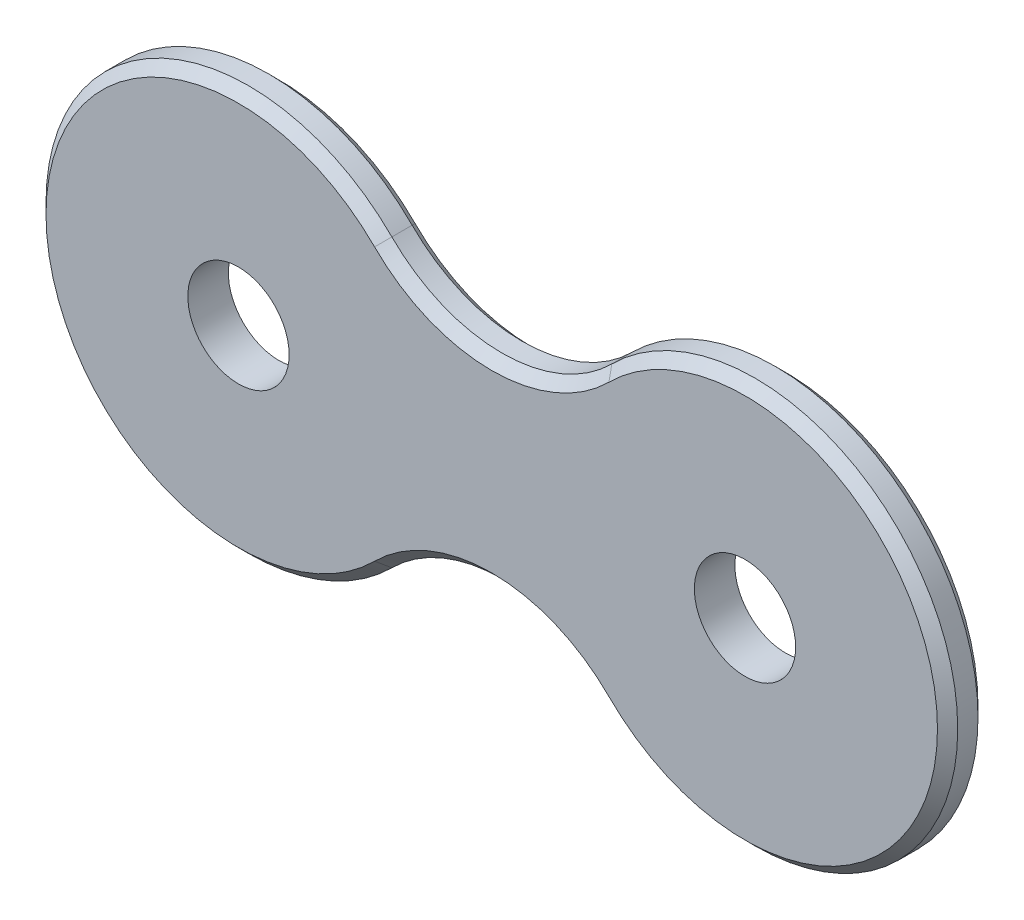
SolidWorks part; units mm, degrees
ref_plane "Front Plane" through (0, 0, 0) normal (0, 0, 1) x (1, 0, 0)
ref_plane "Top Plane" through (0, 0, 0) normal (0, 1, 0) x (1, 0, 0)
ref_plane "Right Plane" through (0, 0, 0) normal (1, 0, 0) x (0, 0, -1)
sketch "Sketch1" plane through (0, 0, 0) normal (0, 0, 1) x (1, 0, 0)
  arc A0 (17.9289, -7.0711) -> (17.9289, 7.0711) centre (25, 0) ccw
  circle A1 centre (25, 0) radius 2.5
  arc A2 (7.0711, 7.0711) -> (7.0711, -7.0711) centre (0, 0) ccw
  circle A3 centre (0, 0) radius 2.5
  arc A5 (7.0711, 7.0711) -> (17.9289, 7.0711) centre (12.5, 12.5) ccw
  arc A6 (17.9289, -7.0711) -> (7.0711, -7.0711) centre (12.5, -12.5) ccw
  dimension "D2" = 20
  dimension "D3" = 20
  dimension "D4" = 5
  dimension "D5" = 5
  dimension "D1" = 25
extrude "Boss-Extrude1" add sketch "Sketch1" along normal blind 2 contours A2 A6 A0 A5 | A3 | A1
chamfer "Chamfer1" distance 0.5 angle 45 8 edges at (12.5, -4.8223, 0) (-10, 0, 0) (35, 0, 0) (12.5, 4.8223, 0) (35, 0, 2) (12.5, -4.8223, 2) (-10, 0, 2) (12.5, 4.8223, 2)
